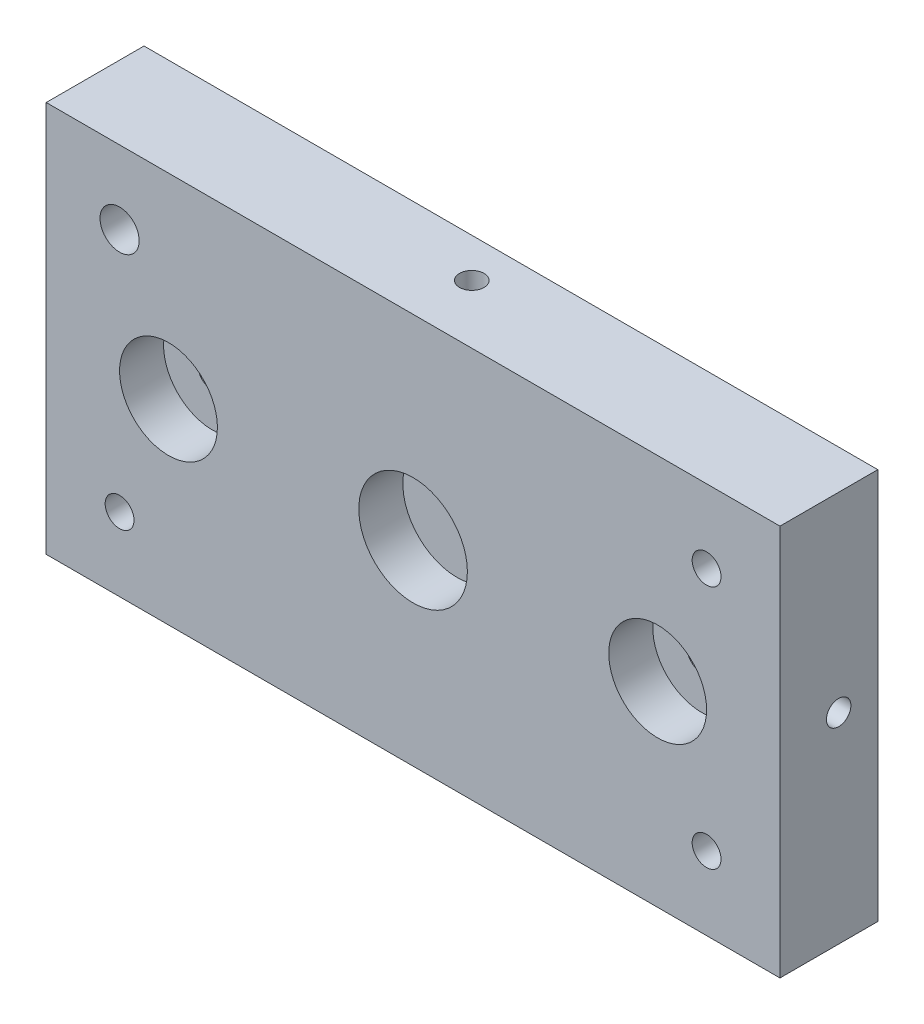
SolidWorks part; units mm, degrees
ref_plane "Front Plane" through (0, 0, 0) normal (0, 0, 1) x (1, 0, 0)
ref_plane "Top Plane" through (0, 0, 0) normal (0, 1, 0) x (1, 0, 0)
ref_plane "Right Plane" through (0, 0, 0) normal (1, 0, 0) x (0, 0, -1)
sketch "Sketch1" plane through (0, 0, 0) normal (0, 0, 1) x (1, 0, 0)
  line L0 (-75, 0) -> (75, 0) construction
  line L1 (75, -40) -> (-75, -40)
  line L2 (75, -40) -> (75, 40)
  line L3 (75, 40) -> (-75, 40)
  line L4 (-75, -40) -> (-75, 40)
  line L5 (75, -40) -> (-75, 40) construction
  line L6 (75, 40) -> (-75, -40) construction
  line L7 (0, 0) -> (0, 40) construction
  point P0 (0, 0)
  dimension "D1" = 80
  dimension "D2" = 150
extrude "Boss-Extrude1" add sketch "Sketch1" along normal blind 20
sketch "Sketch2" plane through (0, 0, 20) normal (0, 0, 1) x (1, 0, 0)
  line L0 (-75, 0) -> (75, 0) construction
  line L1 (-75, 40) -> (-75, -40) construction
  line L2 (75, -40) -> (75, 40) construction
  line L3 (0, 0) -> (0, 40) construction
  line L4 (75, 40) -> (-75, 40) construction
  circle A1 centre (-50, 0) radius 3
  circle A2 centre (50, 0) radius 3
  dimension "D1" = 100
  dimension "D2" = 6
extrude "Cut-Extrude1" cut sketch "Sketch2" against normal up to next
sketch "Sketch3" plane through (0, 0, 20) normal (0, 0, 1) x (1, 0, 0)
  circle A0 centre (0, 0) radius 11.1
  circle A1 centre (-50, 0) radius 10
  circle A2 centre (50, 0) radius 10
  dimension "D1" = 22.2
  dimension "D2" = 20
  dimension "D3" = 20
extrude "Cut-Extrude2" cut sketch "Sketch3" against normal blind 9
sketch "Sketch4" plane through (0, 0, 20) normal (0, 0, 1) x (1, 0, 0)
  circle A0 centre (-60, 25) radius 4
  circle A1 centre (60, 25) radius 2.9496
  circle A2 centre (60, -25) radius 2.9496
  circle A3 centre (-60, -25) radius 2.9496
  dimension "D3" = 8
  dimension "D1" = 120
  dimension "D2" = 50
extrude "Cut-Extrude3" cut sketch "Sketch4" against normal up to next
sketch "Sketch5" plane through (0, 0, 0) normal (0, 0, -1) x (-1, 0, 0)
  circle A0 centre (-50, 0) radius 5
  circle A1 centre (50, 0) radius 5
  dimension "D1" = 10
  dimension "D2" = 10
extrude "Cut-Extrude4" cut sketch "Sketch5" against normal blind 5
sketch "Sketch6" plane through (-75, 0, 0) normal (-1, 0, 0) x (0, 0, 1)
  line L0 (20, 1) -> (0, 1) construction
  line L1 (20, 40) -> (20, -40) construction
  line L2 (0, 40) -> (0, -40) construction
  line L3 (20, -40) -> (0, -40) construction
  circle A0 centre (8, 1) radius 2.5
  dimension "D3" = 5
  dimension "D1" = 8
  dimension "D2" = 41
extrude "Cut-Extrude5" cut sketch "Sketch6" against normal blind 10
mirror "Mirror1" about plane through (0, 0, 0) normal (1, 0, 0) of "Cut-Extrude5"
sketch "Sketch7" plane through (0, -40, 0) normal (0, -1, 0) x (1, 0, 0)
  line L0 (0, 20) -> (0, 0) construction
  line L1 (-75, 20) -> (75, 20) construction
  line L2 (-75, 20) -> (-75, 0) construction
  circle A0 centre (-62, 8) radius 2.5
  circle A1 centre (62, 8) radius 2.5
  dimension "D3" = 5
  dimension "D1" = 13
  dimension "D2" = 12
extrude "Cut-Extrude6" cut sketch "Sketch7" against normal blind 10
sketch "Sketch8" plane through (0, 40, 0) normal (0, 1, 0) x (1, 0, 0)
  line L0 (0, 0) -> (0, -20) construction
  line L1 (75, -20) -> (-75, -20) construction
  line L2 (75, 0) -> (-75, 0) construction
  circle A0 centre (0, -8) radius 2.5
  dimension "D1" = 5
  dimension "D2" = 8
extrude "Cut-Extrude7" cut sketch "Sketch8" against normal blind 10
